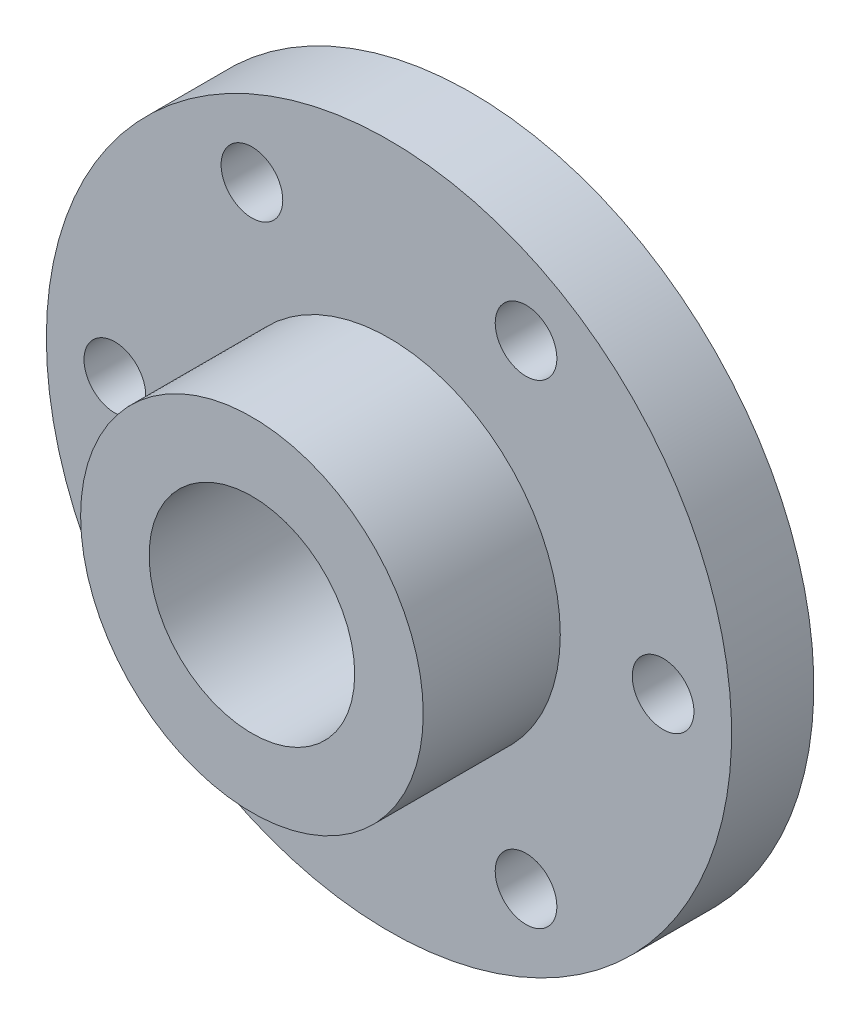
SolidWorks part; units mm, degrees
ref_plane "前视基准面" through (0, 0, 0) normal (0, 0, 1) x (1, 0, 0)
ref_plane "上视基准面" through (0, 0, 0) normal (0, 1, 0) x (1, 0, 0)
ref_plane "右视基准面" through (0, 0, 0) normal (1, 0, 0) x (0, 0, -1)
sketch "草图1" plane through (0, 0, 0) normal (0, 1, 0) x (1, 0, 0)
  line L0 (0, 0) -> (0, -32) construction
  line L1 (0, 0) -> (50, 0)
  line L2 (50, 0) -> (50, -12)
  line L3 (50, -12) -> (25, -12)
  line L4 (25, -12) -> (25, -32)
  line L5 (25, -32) -> (0, -32)
  line L6 (0, -32) -> (0, 0)
revolve "旋转1" add sketch "草图1" angle 360 about L0
sketch "草图2" plane through (0, 0, 0) normal (0, 0, 1) x (1, 0, 0)
  circle A0 centre (0, 0) radius 15
extrude "切除-拉伸1" cut sketch "草图2" along normal through all
sketch "草图3" plane through (0, 0, 0) normal (0, 0, 1) x (1, 0, 0)
  circle A0 centre (0, 0) radius 35
extrude "切除-拉伸2" cut sketch "草图3" along normal blind 3
ref_plane "基准面1" through (0, 0, 32) normal (0, 0, 1) x (1, 0, 0)
sketch "草图4" plane through (0, 0, 32) normal (0, 0, 1) x (1, 0, 0)
  circle A0 centre (40, 0) radius 4.5
  circle A1 centre (20, 34.641) radius 4.5
  circle A2 centre (-20, 34.641) radius 4.5
  circle A3 centre (-40, 0) radius 4.5
  circle A4 centre (-20, -34.641) radius 4.5
  circle A5 centre (20, -34.641) radius 4.5
extrude "切除-拉伸3" cut sketch "草图4" against normal through all
